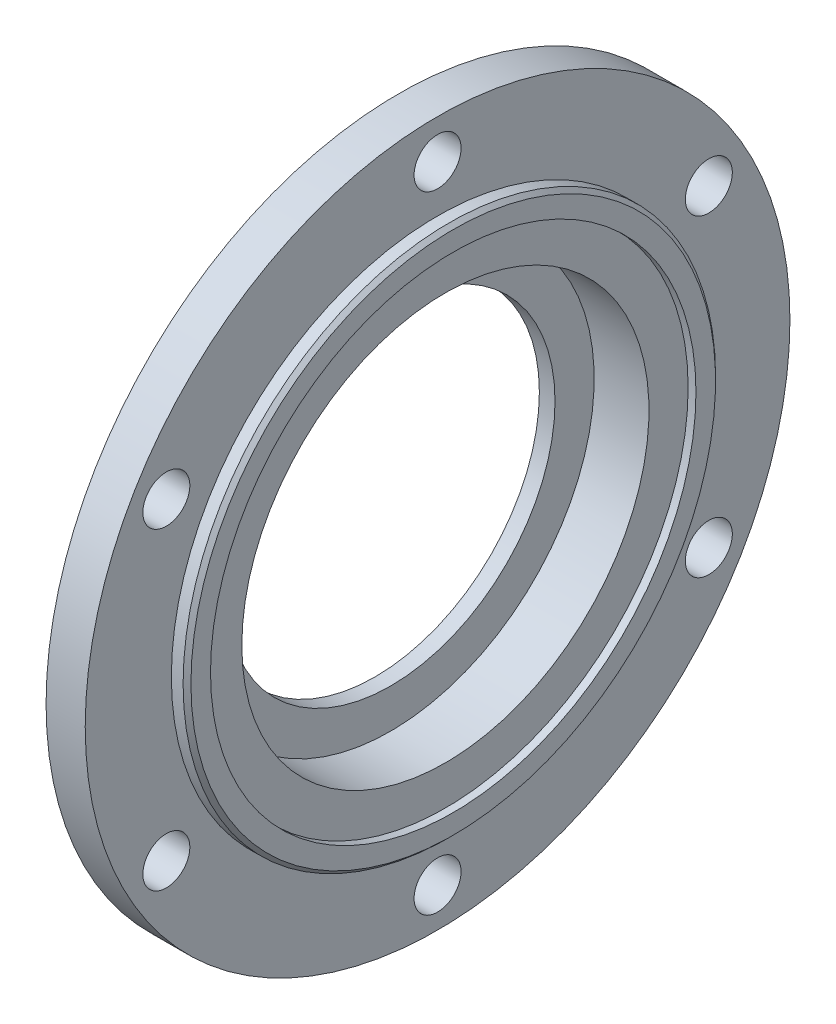
SolidWorks part; units mm, degrees
ref_plane "Front Plane" through (0, 0, 0) normal (0, 0, 1) x (1, 0, 0)
ref_plane "Top Plane" through (0, 0, 0) normal (0, 1, 0) x (1, 0, 0)
ref_plane "Right Plane" through (0, 0, 0) normal (1, 0, 0) x (0, 0, -1)
sketch "Sketch1" plane through (0, 0, 0) normal (0, 1, 0) x (1, 0, 0)
  line L0 (0, 0) -> (30.8259, 0) construction
  line L1 (0, 21) -> (0, 31)
  line L2 (0, 31) -> (3, 34)
  line L3 (3, 34) -> (3, 45)
  line L4 (3, 45) -> (8, 45)
  line L5 (8, 45) -> (8, 34)
  line L6 (8, 34) -> (9.5, 34)
  line L7 (10, 33.5) -> (10, 31)
  line L8 (10, 31) -> (9, 31)
  line L9 (9, 31) -> (9, 26)
  line L10 (9, 26) -> (2, 26)
  line L11 (2, 26) -> (2, 21)
  line L12 (2, 21) -> (0, 21)
  line L13 (9.5, 34) -> (10, 33.5)
  point P7 (0, 0)
  point P10 (10, 34)
  point P17 (1.826, 6.2052)
  point P19 (0, 0)
  dimension "D1" = 2
  dimension "D2" = 10
  dimension "D3" = 7
  dimension "D4" = 3
  dimension "D5" = 45
  dimension "D6" = 2
  dimension "D7" = 90
  dimension "D8" = 0.5
  dimension "D9" = 45
  dimension "D10" = 5
  dimension "D11" = 68
  dimension "D12" = 42
  dimension "D13" = 52
  dimension "D14" = 62
revolve "Revolve1" add sketch "Sketch1" angle 360 about L0
sketch "Sketch2" plane through (3, 0, 0) normal (-1, 0, 0) x (0, 0, 1)
  circle A0 centre (0, 0) radius 40 construction
  circle A1 centre (0, 40) radius 3
  circle A2 centre (34.641, 20) radius 3
  circle A3 centre (34.641, -20) radius 3
  circle A4 centre (0, -40) radius 3
  circle A5 centre (-34.641, -20) radius 3
  circle A6 centre (-34.641, 20) radius 3
  point P17 (0, 0)
  dimension "D1" = 6
extrude "Cut-Extrude1" cut sketch "Sketch2" against normal blind 10
